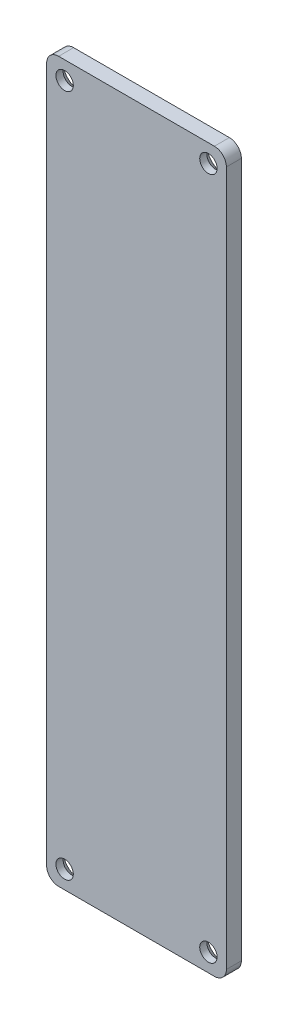
SolidWorks part; units mm, degrees
ref_plane "Front Plane" through (0, 0, 0) normal (0, 0, 1) x (1, 0, 0)
ref_plane "Top Plane" through (0, 0, 0) normal (0, 1, 0) x (1, 0, 0)
ref_plane "Right Plane" through (0, 0, 0) normal (1, 0, 0) x (0, 0, -1)
sketch "Sketch1" plane through (0, 0, 0) normal (0, 0, 1) x (1, 0, 0)
  line L0 (-63.1226, 90.4321) -> (-63.1226, -25.5679)
  line L1 (-91.1226, -27.5679) -> (-65.1226, -27.5679)
  line L2 (-93.1226, -25.5679) -> (-93.1226, 90.4321)
  line L3 (-91.1226, 92.4321) -> (-65.1226, 92.4321)
  arc A0 (-91.1226, -27.5679) -> (-93.1226, -25.5679) centre (-91.1226, -25.5679) cw
  arc A3 (-93.1226, 90.4321) -> (-91.1226, 92.4321) centre (-91.1226, 90.4321) cw
  arc A6 (-65.1226, 92.4321) -> (-63.1226, 90.4321) centre (-65.1226, 90.4321) cw
  arc A7 (-65.1226, -27.5679) -> (-63.1226, -25.5679) centre (-65.1226, -25.5679) ccw
  point P6 (-93.1226, -27.5679)
  point P23 (-63.1226, 92.4321)
  point P26 (-63.1226, -27.5679)
  dimension "D3" = 2
  dimension "D1" = 116
  dimension "D2" = 26
extrude "Boss-Extrude1" add sketch "Sketch1" along normal blind 2.5
hole_wizard "CSK for M2.5 Countersunk Flat Head Screw2" positions "3DSketch2" profile "Sketch3" countersink size "M2.5" standard "ISO" end condition through all
sketch3d "3DSketch2"
  line L0 (-65.1226, 92.4321, 0) -> (-91.1226, 92.4321, 0) construction
  line L2 (-93.1226, 90.4321, 0) -> (-93.1226, -25.5679, 0) construction
  line L4 (-91.1226, -27.5679, 0) -> (-65.1226, -27.5679, 0) construction
  line L5 (-63.1226, -25.5679, 0) -> (-63.1226, 90.4321, 0) construction
  point P0 (-66.1226, 89.4321, 0)
  point P2 (-90.1226, 89.4321, 0)
  point P4 (-66.1226, -24.5679, 0)
  point P6 (-90.1226, -24.5679, 0)
  dimension "D1" = 3
  dimension "D2" = 3
  dimension "D3" = 3
  dimension "D4" = 3
sketch "Sketch3" plane through (-66.1226, 89.4321, 0) normal (1, 0, 0) x (0, 1, 0)
  line L0 (0, 0) -> (0, 2.5)
  line L1 (0, 2.5) -> (1.45, 2.5)
  line L2 (1.45, 2.5) -> (1.45, 1.3)
  line L3 (1.45, 1.3) -> (2.75, 0)
  line L5 (2.75, 0) -> (0, 0)
  line L6 (-1.45, 1.3) -> (-2.75, 0) construction
  line L11 (0, -6.35) -> (0, 107.95) construction
  dimension "Thru Hole Dia." = 2.9
  dimension "Thru Hole Depth" = 2.5
  dimension "Near C'Sink Dia." = 5.5
  dimension "Near C'Sink Angle" = 90
